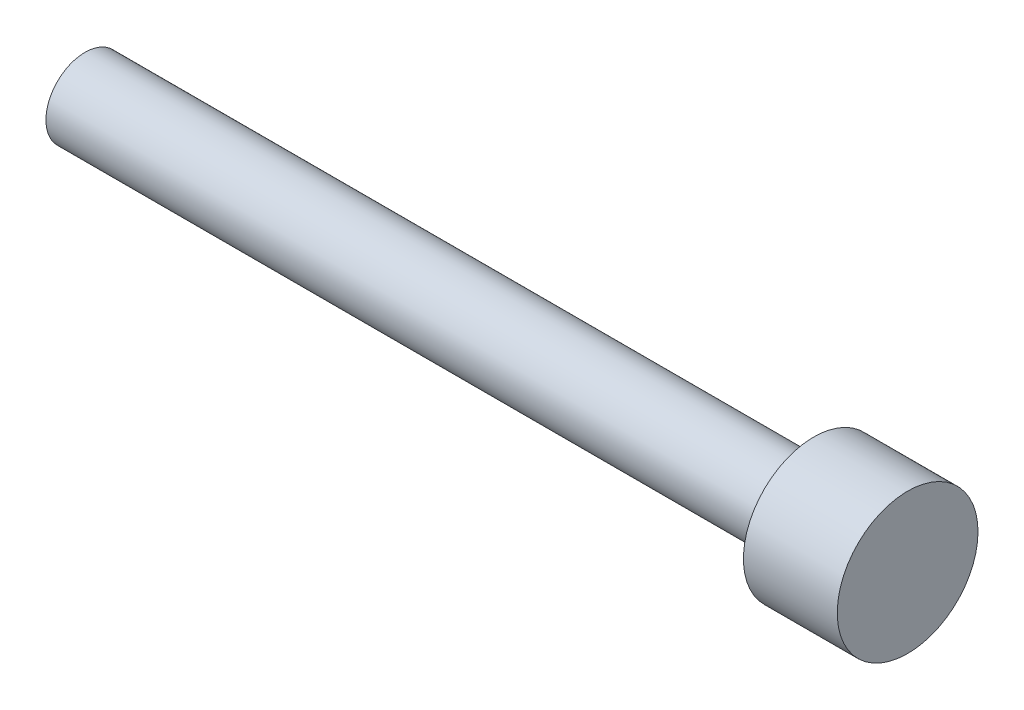
SolidWorks part; units mm, degrees
ref_plane "Front Plane" through (0, 0, 0) normal (0, 0, 1) x (1, 0, 0)
ref_plane "Top Plane" through (0, 0, 0) normal (0, 1, 0) x (1, 0, 0)
ref_plane "Right Plane" through (0, 0, 0) normal (1, 0, 0) x (0, 0, -1)
sketch "Sketch1" plane through (0, 0, 0) normal (1, 0, 0) x (0, 0, -1)
  circle A0 centre (0, 0) radius 1.25
  dimension "D1" = 2.5
extrude "Boss-Extrude1" add sketch "Sketch1" along normal mid plane 23.3
sketch "Sketch2" plane through (11.65, 0, 0) normal (1, 0, 0) x (0, 0, -1)
  circle A0 centre (0, 0) radius 2.25
  dimension "D1" = 4.5
extrude "Boss-Extrude2" add sketch "Sketch2" along normal blind 3
